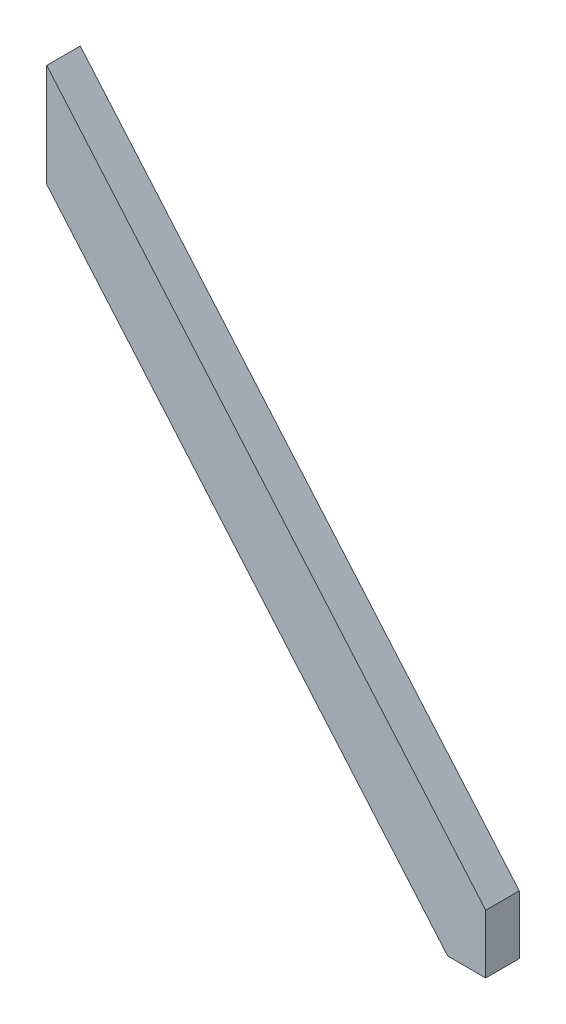
SolidWorks part; units mm, degrees
material "Pine"
ref_plane "Front Plane" through (0, 0, 0) normal (0, 0, 1) x (1, 0, 0)
ref_plane "Top Plane" through (0, 0, 0) normal (0, 1, 0) x (1, 0, 0)
ref_plane "Right Plane" through (0, 0, 0) normal (1, 0, 0) x (0, 0, -1)
sketch "Sketch1" plane through (0, 0, 0) normal (0, 0, 1) x (1, 0, 0)
  line L0 (-57.6147, -44.45) -> (-665, 664.15)
  line L1 (-2286, 664.15) -> (0, 664.15) construction
  line L4 (-665, 820.2656) -> (0, 44.45)
  line L5 (0, -44.45) -> (0, 44.45)
  line L7 (0, -44.45) -> (-57.6147, -44.45)
  line L8 (-2286, -44.45) -> (0, -44.45) construction
  line L9 (-665, 664.15) -> (-665, 820.2656)
  line L10 (-665, 1291.8) -> (-665, -583.2) construction
  dimension "D1" = 101.6
extrude "Boss-Extrude1" add sketch "Sketch1" along normal blind 50.8
